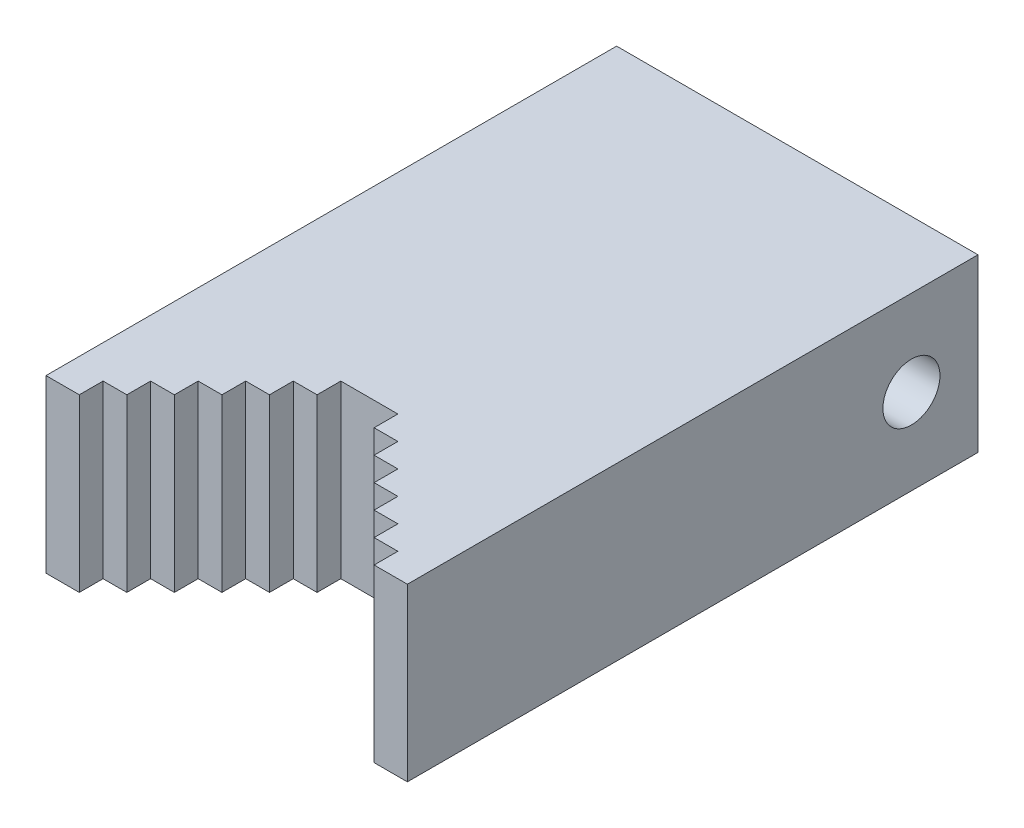
SolidWorks part; units mm, degrees
ref_plane "Front Plane" through (0, 0, 0) normal (0, 0, 1) x (1, 0, 0)
ref_plane "Top Plane" through (0, 0, 0) normal (0, 1, 0) x (1, 0, 0)
ref_plane "Right Plane" through (0, 0, 0) normal (1, 0, 0) x (0, 0, -1)
sketch "Sketch1" plane through (0, 0, 0) normal (0, 1, 0) x (1, 0, 0)
  line L0 (0, 0) -> (3.5, 0)
  line L1 (0, 0) -> (38, 0)
  line L2 (0, 0) -> (0, 60)
  line L3 (0, 60) -> (38, 60)
  line L4 (38, 0) -> (38, 60)
  line L5 (3.5, 0) -> (3.5, 2.5)
  line L6 (3.5, 2.5) -> (6, 2.5)
  line L7 (6, 2.5) -> (6, 5)
  line L8 (6, 5) -> (8.5, 5)
  line L9 (8.5, 5) -> (8.5, 7.5)
  line L10 (8.5, 7.5) -> (11, 7.5)
  line L11 (11, 7.5) -> (11, 10)
  line L12 (11, 10) -> (13.5, 10)
  line L13 (13.5, 10) -> (13.5, 12.5)
  line L14 (13.5, 12.5) -> (16, 12.5)
  line L15 (16, 12.5) -> (16, 15)
  line L16 (16, 15) -> (22, 15)
  line L17 (19, 15) -> (19, 0) construction
  line L18 (38, 0) -> (34.5, 0)
  line L19 (34.5, 0) -> (34.5, 2.5)
  line L20 (34.5, 2.5) -> (32, 2.5)
  line L21 (32, 2.5) -> (32, 5)
  line L22 (32, 5) -> (29.5, 5)
  line L23 (29.5, 5) -> (29.5, 7.5)
  line L24 (29.5, 7.5) -> (27, 7.5)
  line L25 (27, 7.5) -> (27, 10)
  line L26 (27, 10) -> (24.5, 10)
  line L27 (24.5, 10) -> (24.5, 12.5)
  line L28 (24.5, 12.5) -> (22, 12.5)
  line L29 (22, 12.5) -> (22, 15)
  dimension "D1" = 60
  dimension "D2" = 38
  dimension "D3" = 2.5
  dimension "D4" = 2.5
  dimension "D5" = 2.5
  dimension "D6" = 2.5
  dimension "D7" = 2.5
  dimension "D8" = 2.5
  dimension "D9" = 3.5
  dimension "D10" = 6
extrude "Boss-Extrude1" add sketch "Sketch1" along normal blind 18 contours L29 L28 L27 L26 L25 L24 L23 L22 L21 L20 L19 L1 L4 L3 L2 L0 L5 L6 L7 L8 L9 L10 L11 L12 L13 L14 L15 L16
sketch "Sketch2" plane through (38, 0, 0) normal (1, 0, 0) x (0, 0, -1)
  line L0 (60, 18) -> (60, 0) construction
  circle A0 centre (53, 9) radius 3
  point P2 (60, 9)
  dimension "D1" = 7
extrude "Cut-Extrude1" cut sketch "Sketch2" against normal blind 38
hole_wizard "Ø12.0mm Dowel Hole1" positions "3DSketch1" profile "Sketch4" hole size "Ø12.0" standard "ISO"
sketch3d "3DSketch1"
  line L0 (38, 18, -60) -> (38, 0, -60) construction
  line L1 (0, 18, -60) -> (38, 18, -60) construction
  point P0 (19, 9, -60)
  dimension "D1" = 19
  dimension "D2" = 9
sketch "Sketch4" plane through (19, 9, -60) normal (1, 0, 0) x (0, 1, 0)
  line L0 (0, 0) -> (0, 23.6052)
  line L1 (0, 23.6052) -> (6, 20)
  line L2 (6, 20) -> (6, 0)
  line L5 (6, 0) -> (0, 0)
  line L10 (0, 23.6052) -> (-6, 20) construction
  line L11 (0, -6.35) -> (0, 107.95) construction
  dimension "Hole Dia." = 12
  dimension "Hole Depth" = 20
  dimension "Drill Angle" = 118
